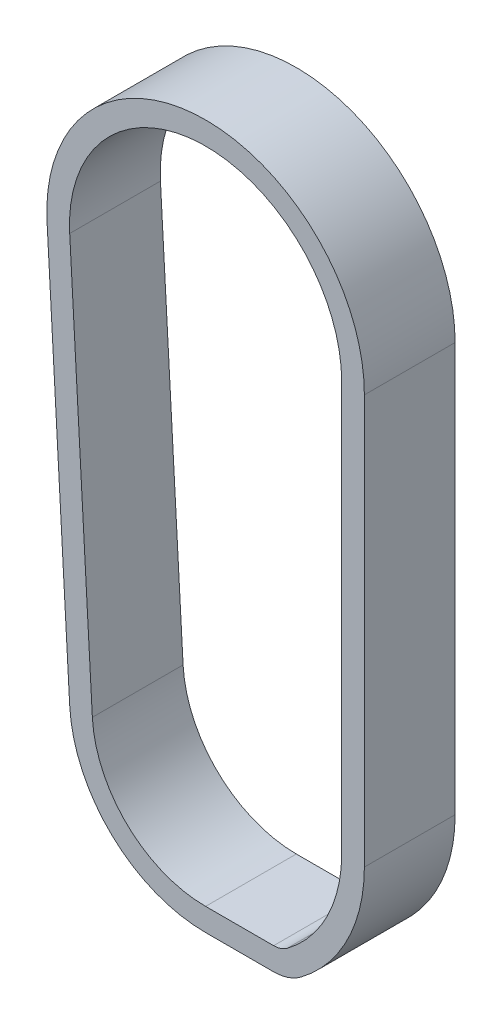
SolidWorks part; units mm, degrees
ref_plane "Front Plane" through (0, 0, 0) normal (0, 0, 1) x (1, 0, 0)
ref_plane "Top Plane" through (0, 0, 0) normal (0, 1, 0) x (1, 0, 0)
ref_plane "Right Plane" through (0, 0, 0) normal (1, 0, 0) x (0, 0, -1)
sketch "Sketch1" plane through (0, 0, 0) normal (0, 0, 1) x (1, 0, 0)
  line L0 (30, -90.14) -> (30, 0)
  line L1 (-29.9538, -1.6641) -> (-24.9615, -91.5267)
  line L2 (0, -115.14) -> (15, -115.14)
  line L6 (35, -90.14) -> (35, 0)
  line L7 (-34.9461, -1.9414) -> (-29.9538, -91.8041)
  line L8 (0, -120.14) -> (15, -120.14)
  arc A0 (30, 0) -> (-29.9538, -1.6641) centre (0, 0) ccw
  arc A1 (-24.9615, -91.5267) -> (0, -115.14) centre (0, -90.14) ccw
  arc A2 (15, -115.14) -> (18, -114.14) centre (15, -110.14) ccw
  arc A3 (18, -114.14) -> (30, -90.14) centre (0, -90.14) ccw
  arc A8 (35, 0) -> (-34.9461, -1.9414) centre (0, 0) ccw
  arc A9 (-29.9538, -91.8041) -> (0, -120.14) centre (0, -90.14) ccw
  arc A10 (15, -120.14) -> (21, -118.14) centre (15, -110.14) ccw
  arc A11 (21, -118.14) -> (35, -90.14) centre (0, -90.14) ccw
  dimension "D1" = 5
extrude "Boss-Extrude1" add sketch "Sketch1" along normal blind 20
